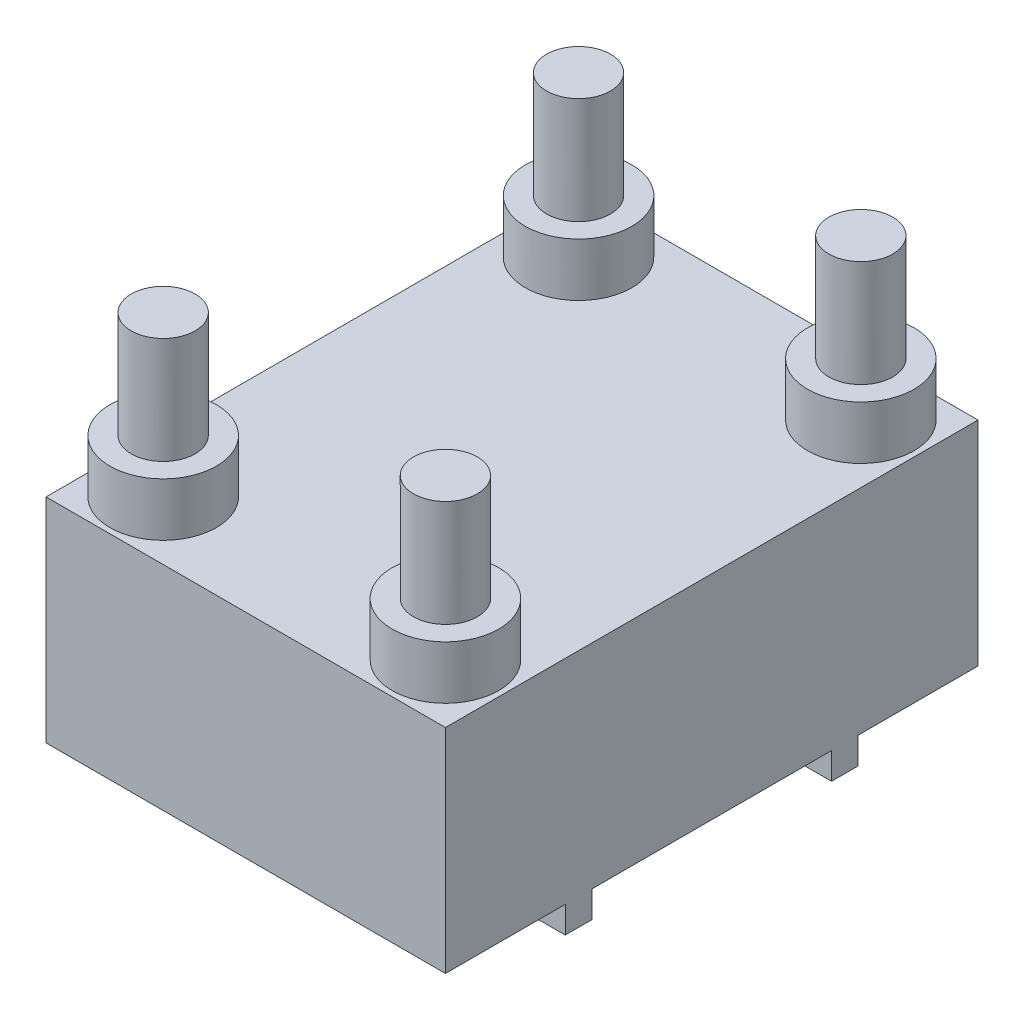
SolidWorks part; units mm, degrees
ref_plane "Alzado" through (0, 0, 0) normal (0, 0, 1) x (1, 0, 0)
ref_plane "Planta" through (0, 0, 0) normal (0, 1, 0) x (1, 0, 0)
ref_plane "Vista lateral" through (0, 0, 0) normal (1, 0, 0) x (0, 0, -1)
sketch "Croquis2" plane through (0, 0, 0) normal (0, 1, 0) x (1, 0, 0)
  line L1 (37.5, 50) -> (-37.5, 50)
  line L2 (37.5, 50) -> (37.5, -50)
  line L3 (37.5, -50) -> (-37.5, -50)
  line L4 (-37.5, 50) -> (-37.5, -50)
  line L5 (37.5, 50) -> (-37.5, -50) construction
  line L6 (37.5, -50) -> (-37.5, 50) construction
  point P0 (0, 0)
  dimension "D1" = 75
  dimension "D2" = 100
extrude "Saliente-Extruir1" add sketch "Croquis2" along normal blind 40
sketch "Croquis3" plane through (0, 0, 0) normal (0, -1, 0) x (1, 0, 0)
  line L0 (-37.5, 25) -> (37.5, 25) construction
  line L1 (-37.5, -50) -> (-37.5, 50) construction
  line L2 (37.5, 50) -> (37.5, -50) construction
  line L3 (-37.5, 0) -> (37.5, 0) construction
  line L4 (-37.5, -25) -> (37.5, -25) construction
  line L6 (-37.5, 50) -> (37.5, 50) construction
  line L7 (37.5, -50) -> (-37.5, -50) construction
  line L9 (37.5, 27.5) -> (-37.5, 27.5)
  line L10 (37.5, 27.5) -> (37.5, 22.5)
  line L11 (37.5, 22.5) -> (-37.5, 22.5)
  line L12 (-37.5, 27.5) -> (-37.5, 22.5)
  line L13 (37.5, 27.5) -> (-37.5, 22.5) construction
  line L14 (37.5, 22.5) -> (-37.5, 27.5) construction
  line L15 (37.5, -22.5) -> (-37.5, -22.5)
  line L16 (37.5, -22.5) -> (37.5, -27.5)
  line L17 (37.5, -27.5) -> (-37.5, -27.5)
  line L18 (-37.5, -22.5) -> (-37.5, -27.5)
  line L19 (37.5, -22.5) -> (-37.5, -27.5) construction
  line L20 (37.5, -27.5) -> (-37.5, -22.5) construction
  point P15 (0, 25)
  point P16 (0, -25)
  point P17 (0, 25)
  point P22 (0, -25)
  dimension "D1" = 25
  dimension "D2" = 25
  dimension "D3" = 5
  dimension "D4" = 5
extrude "Saliente-Extruir2" add sketch "Croquis3" along normal blind 5 contours L10 L9 L12 L11 | L16 L15 L18 L17
sketch "Croquis4" plane through (0, 40, 0) normal (0, 1, 0) x (1, 0, 0)
  line L0 (72.6417, 0) -> (-72.6417, 0) construction
  line L1 (0, 55.9753) -> (0, -55.9753) construction
  line L2 (-37.5, 50) -> (-37.5, -50) construction
  line L3 (37.5, 50) -> (-37.5, 50) construction
  circle A0 centre (-26.5, 39) radius 10
  circle A1 centre (-26.5, 39) radius 6
  circle A2 centre (26.5, 39) radius 6
  circle A3 centre (26.5, 39) radius 10
  circle A4 centre (26.5, -39) radius 10
  circle A5 centre (26.5, -39) radius 6
  circle A6 centre (-26.5, -39) radius 6
  circle A7 centre (-26.5, -39) radius 10
  point P7 (0, 0)
  point P11 (0, 0)
  dimension "D1" = 20
  dimension "D2" = 11
  dimension "D4" = 12
  dimension "D3" = 11
extrude "Saliente-Extruir7" add sketch "Croquis4" along normal blind 10
sketch "Croquis9" plane through (0, 40, 0) normal (0, 1, 0) x (1, 0, 0)
  line L0 (0, 0) -> (0, -11.6983) construction
  line L1 (0, 0) -> (11.8339, 0) construction
  circle A2 centre (-26.5, -39) radius 6
  circle A5 centre (-26.5, -39) radius 10 construction
  circle A6 centre (-26.5, 39) radius 6
  circle A7 centre (26.5, -39) radius 6
  circle A8 centre (26.5, 39) radius 6
  dimension "D1" = 12
extrude "Saliente-Extruir8" add sketch "Croquis9" along normal blind 30
